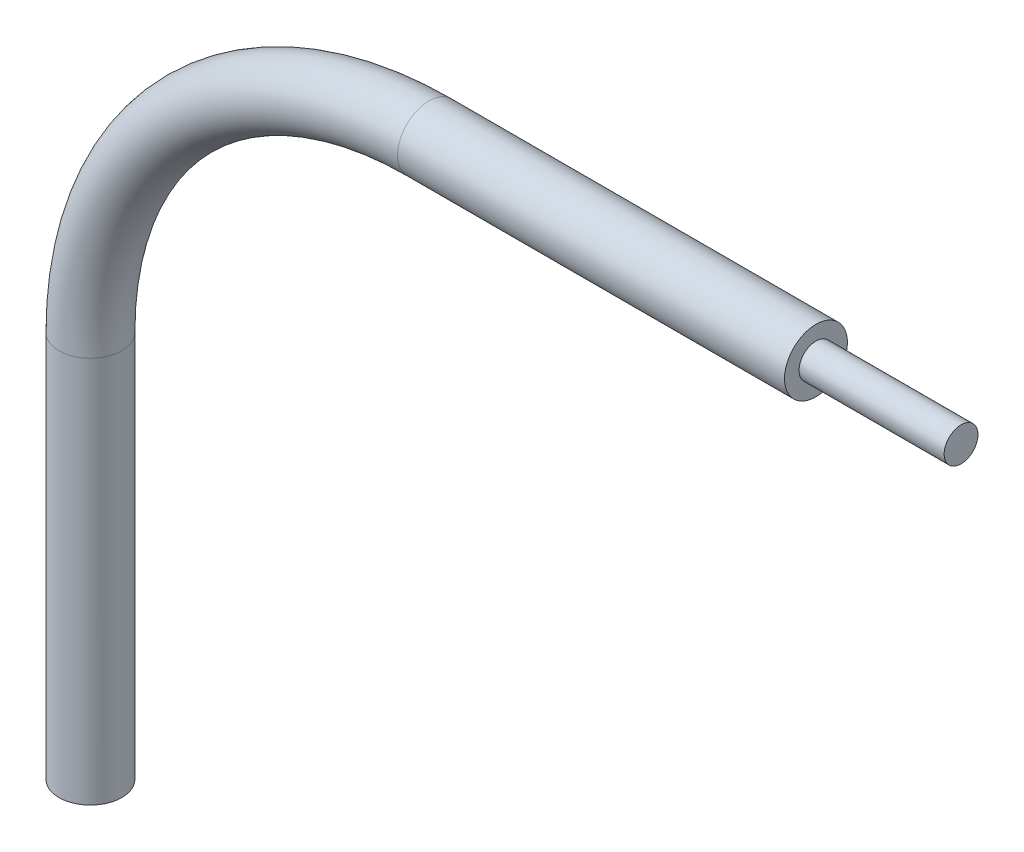
SolidWorks part; units mm, degrees
ref_plane "Front Plane" through (0, 0, 0) normal (0, 0, 1) x (1, 0, 0)
ref_plane "Top Plane" through (0, 0, 0) normal (0, 1, 0) x (1, 0, 0)
ref_plane "Right Plane" through (0, 0, 0) normal (1, 0, 0) x (0, 0, -1)
sketch "Sketch1" plane through (0, 0, 0) normal (0, 0, 1) x (1, 0, 0)
  line L0 (0, 0) -> (0, 8)
  line L1 (7, 15) -> (15, 15)
  arc A0 (0, 8) -> (7, 15) centre (7, 8) cw
  point P5 (0, 0)
  point P7 (0, 0)
  dimension "D1" = 7
  dimension "D2" = 8
  dimension "D3" = 8
sweep "Sweep1" add path "Sketch1" circular profile diameter 1.3 parameters "D3"=1.3
sketch "Sketch9" plane through (15, 0, 0) normal (1, 0, 0) x (0, 0, -1)
  circle A0 centre (0, 15) radius 0.35
  dimension "D1" = 0.7
extrude "Boss-Extrude1" add sketch "Sketch9" along normal blind 3
